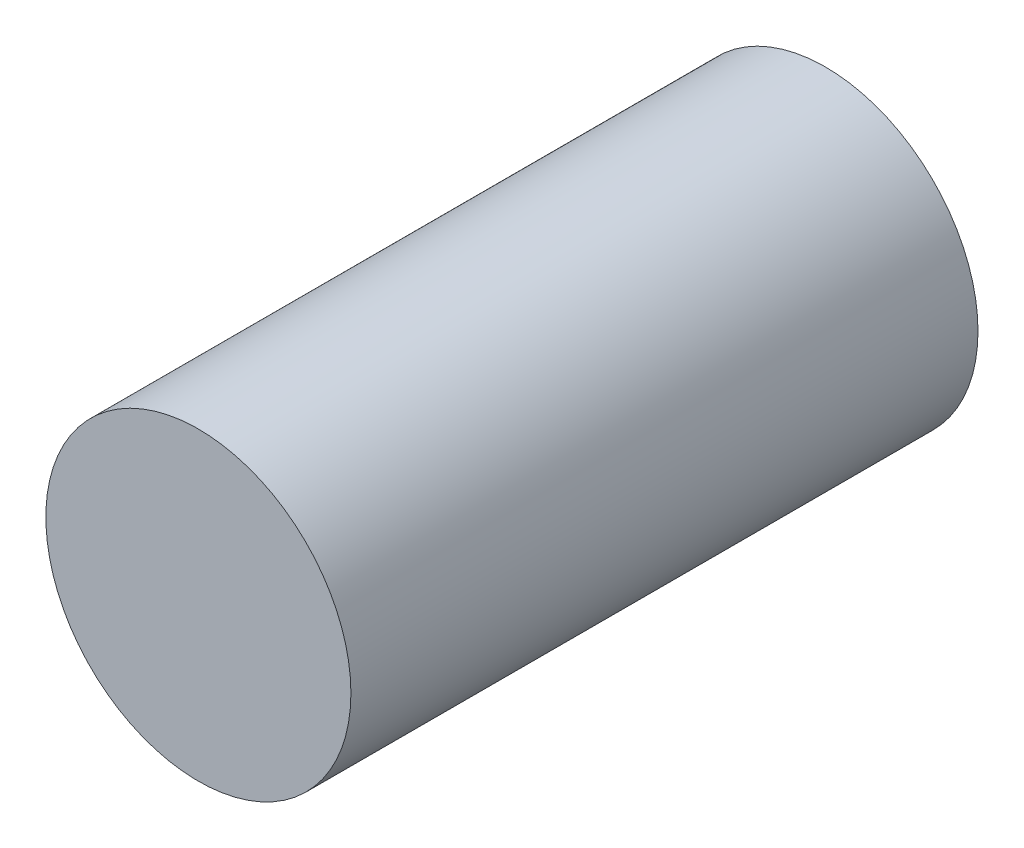
SolidWorks part; units mm, degrees
ref_plane "Front Plane" through (0, 0, 0) normal (0, 0, 1) x (1, 0, 0)
ref_plane "Top Plane" through (0, 0, 0) normal (0, 1, 0) x (1, 0, 0)
ref_plane "Right Plane" through (0, 0, 0) normal (1, 0, 0) x (0, 0, -1)
sketch "Sketch1" plane through (0, 0, 0) normal (0, 0, 1) x (1, 0, 0)
  circle A0 centre (0, 0) radius 18
  dimension "D1" = 36
extrude "Boss-Extrude1" add sketch "Sketch1" against normal blind 74
equation "\"D1@Boss-Extrude1\"=74mm"
